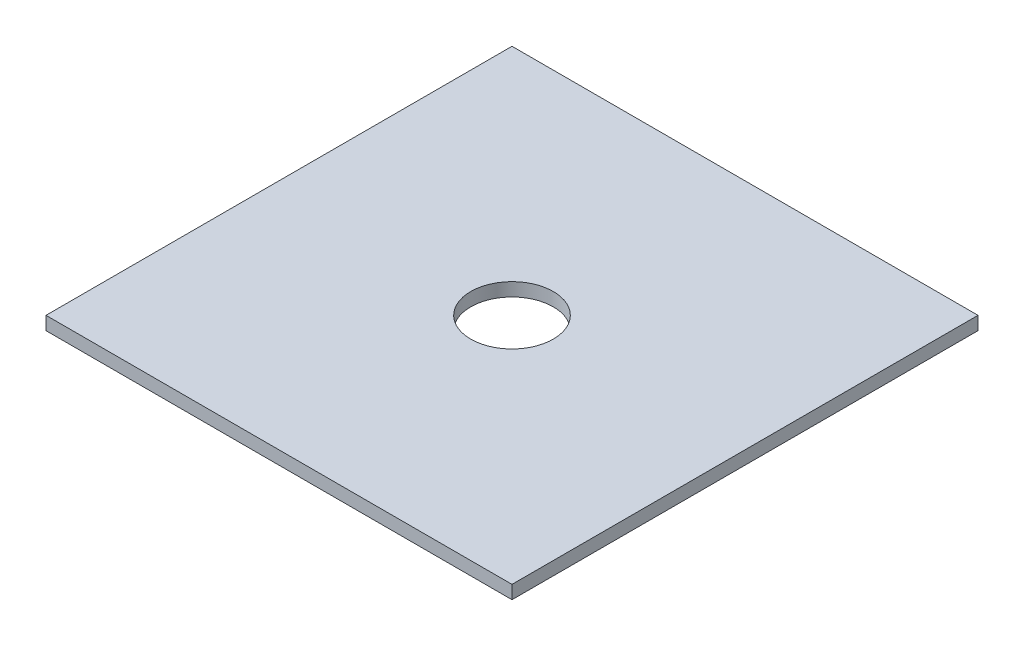
SolidWorks part; units mm, degrees
ref_plane "Front Plane" through (0, 0, 0) normal (0, 0, 1) x (1, 0, 0)
ref_plane "Top Plane" through (0, 0, 0) normal (0, 1, 0) x (1, 0, 0)
ref_plane "Right Plane" through (0, 0, 0) normal (1, 0, 0) x (0, 0, -1)
sketch "Sketch2" plane through (0, 0, 0) normal (0, 1, 0) x (1, 0, 0)
  line L1 (-17.5, 17.5) -> (17.5, 17.5)
  line L2 (-17.5, 17.5) -> (-17.5, -17.5)
  line L3 (-17.5, -17.5) -> (17.5, -17.5)
  line L4 (17.5, 17.5) -> (17.5, -17.5)
  line L5 (-17.5, 17.5) -> (17.5, -17.5) construction
  line L6 (-17.5, -17.5) -> (17.5, 17.5) construction
  point P0 (0, 0)
  dimension "D1" = 35
  dimension "D2" = 35
extrude "Boss-Extrude1" add sketch "Sketch2" along normal blind 10 contours L2 L1 L4 L3
sketch "Sketch3" plane through (0, 10, 0) normal (0, 1, 0) x (1, 0, 0)
  line L1 (-17.5, 17.5) -> (17.5, 17.5)
  line L2 (-17.5, 17.5) -> (-17.5, -17.5)
  line L3 (-17.5, -17.5) -> (17.5, -17.5)
  line L4 (17.5, 17.5) -> (17.5, -17.5)
  line L5 (-17.5, 17.5) -> (17.5, -17.5) construction
  line L6 (-17.5, -17.5) -> (17.5, 17.5) construction
  line L7 (-12.5, 12.5) -> (12.5, 12.5)
  line L8 (-12.5, 12.5) -> (-12.5, -12.5)
  line L9 (-12.5, -12.5) -> (12.5, -12.5)
  line L10 (12.5, 12.5) -> (12.5, -12.5)
  line L11 (-12.5, 12.5) -> (12.5, -12.5) construction
  line L12 (-12.5, -12.5) -> (12.5, 12.5) construction
  point P0 (0, 0)
  point P7 (0, 0)
  dimension "D1" = 25
extrude "Boss-Extrude2" add sketch "Sketch3" along normal blind 15 separate body
sketch "Sketch4" plane through (0, 25, 0) normal (0, 1, 0) x (1, 0, 0)
  line L1 (-17.5, 17.5) -> (17.5, 17.5)
  line L2 (-17.5, 17.5) -> (-17.5, -17.5)
  line L3 (-17.5, -17.5) -> (17.5, -17.5)
  line L4 (17.5, 17.5) -> (17.5, -17.5)
  line L5 (-17.5, 17.5) -> (17.5, -17.5) construction
  line L6 (-17.5, -17.5) -> (17.5, 17.5) construction
  point P0 (0, 0)
extrude "Boss-Extrude3" add sketch "Sketch4" along normal blind 15 separate body
sketch "Sketch5" plane through (0, 40, 0) normal (0, 1, 0) x (1, 0, 0)
  circle A0 centre (0, 0) radius 3.05
extrude "Cut-Extrude1" cut sketch "Sketch5" against normal up to surface (40 mm away)
delete or keep bodies "Body-Delete/Keep 2" type delete bodies bodies 102 104
sketch "Sketch6" plane through (0, 0, -17.5) normal (0, 0, -1) x (-1, 0, 0)
  line L1 (-17.5, 25) -> (-10, 25)
  line L2 (-17.5, 25) -> (-17.5, 26.0178)
  line L3 (-17.5, 26.0178) -> (-10, 26.0178)
  line L4 (-10, 25) -> (-10, 26.0178)
  line L5 (17.5, 25) -> (10, 25)
  line L6 (17.5, 25) -> (17.5, 26.2762)
  line L7 (17.5, 26.2762) -> (10, 26.2762)
  line L8 (10, 25) -> (10, 26.2762)
  dimension "D1" = 7.5
  dimension "D2" = 7.5
extrude "Boss-Extrude4" add sketch "Sketch6" along normal blind 10 and the other way blind 40
sketch "Sketch7" plane through (0, 26.2762, 0) normal (0, 1, 0) x (1, 0, 0)
  line L0 (-17.5, 22.5) -> (-10, 22.5) construction
  line L1 (-17.5, 17.5) -> (-17.5, 27.5) construction
  line L2 (-10, 17.5) -> (-10, 27.5) construction
  line L3 (15.1236, 22.5) -> (7.5761, 22.5) construction
  circle A0 centre (-13.75, 22.5) radius 2.76
  circle A1 centre (8.75, 22.5) radius 2.76
  circle A2 centre (8.75, -18) radius 2.76
  circle A3 centre (-13.75, -18) radius 2.76
  dimension "D1" = 5.52
  dimension "D2" = 2
  dimension "D3" = 2
extrude "Cut-Extrude2" cut sketch "Sketch7" against normal blind 10 contours A0 | A1 | A3 | A2
sketch "Sketch8" plane through (0, 40, 0) normal (0, 1, 0) x (1, 0, 0)
  line L0 (17.5, -17.5) -> (17.5, 17.5) construction
  line L1 (-17.5, 17.5) -> (17.5, 17.5)
  line L2 (-17.5, 17.5) -> (-17.5, -17.5)
  line L3 (-17.5, -17.5) -> (17.5, -17.5)
  line L4 (17.5, 17.5) -> (17.5, -17.5)
  line L5 (-17.5, 17.5) -> (17.5, -17.5) construction
  line L6 (-17.5, -17.5) -> (17.5, 17.5) construction
  line L7 (-17.5, -17.5) -> (17.5, -17.5) construction
  point P0 (0, 0)
extrude "Boss-Extrude5" add sketch "Sketch8" along normal blind 1 separate body
sketch "Sketch9" plane through (0, 41, 0) normal (0, 1, 0) x (1, 0, 0)
  circle A0 centre (0, 0) radius 3.1
  dimension "D1" = 6.2
extrude "Cut-Extrude3" cut sketch "Sketch9" against normal blind 1
delete or keep bodies "Body-Delete/Keep 3" type delete bodies bodies 107
